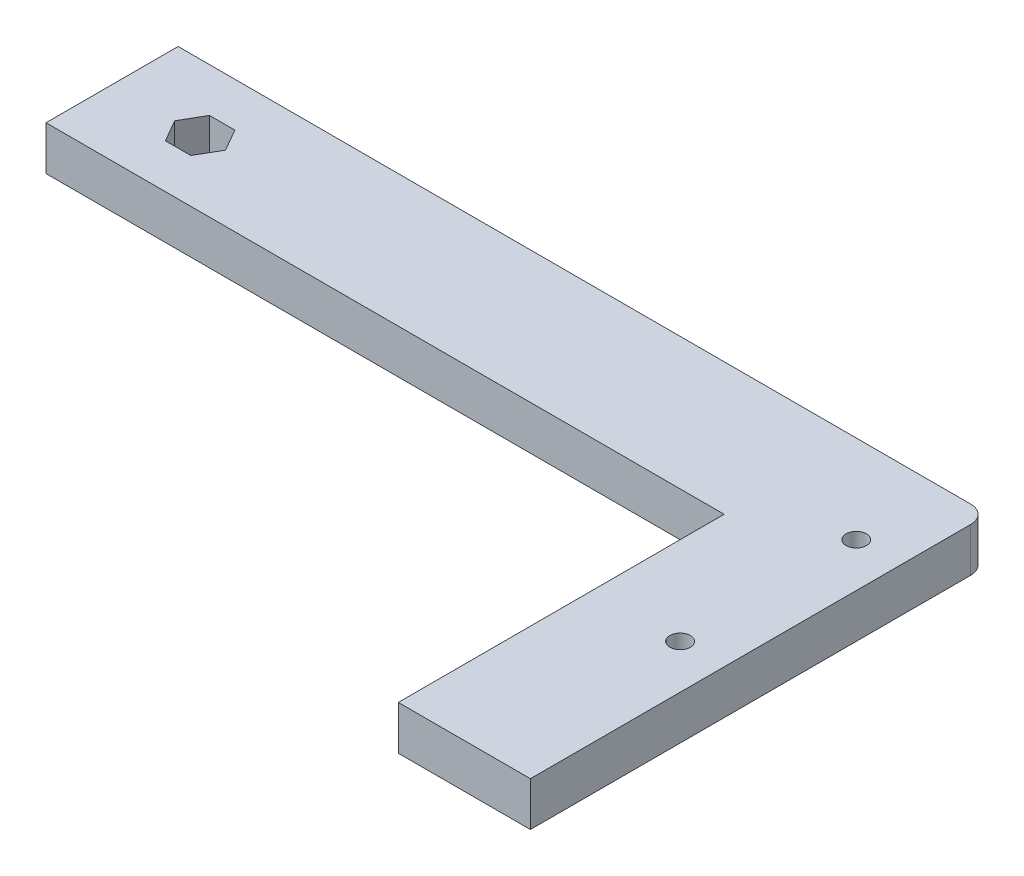
SolidWorks part; units mm, degrees
material "Acrylic (Medium-high impact)"
ref_plane "Front Plane" through (0, 0, 0) normal (0, 0, 1) x (1, 0, 0)
ref_plane "Top Plane" through (0, 0, 0) normal (0, 1, 0) x (1, 0, 0)
ref_plane "Right Plane" through (0, 0, 0) normal (1, 0, 0) x (0, 0, -1)
sketch "Sketch1" plane through (0, 0, 0) normal (0, 1, 0) x (1, 0, 0)
  line L0 (0, 0) -> (114.3, 0)
  line L1 (116.84, -2.54) -> (116.84, -66.04)
  line L2 (0, -19.05) -> (97.79, -19.05)
  line L3 (97.79, -19.05) -> (97.79, -66.04)
  line L4 (0, 0) -> (0, -19.05)
  line L5 (97.79, -19.05) -> (97.79, -66.04) construction
  line L6 (97.79, -66.04) -> (116.84, -66.04)
  arc A0 (114.3, 0) -> (116.84, -2.54) centre (114.3, -2.54) cw
  arc A1 (97.79, -19.05) -> (97.79, -19.05) centre (97.79, -19.05) cw
  dimension "D1" = 2.54
  dimension "D2" = 114.3
  dimension "D3" = 63.5
  dimension "D5" = 90
  dimension "D4" = 19.05
extrude "Boss-Extrude1" add sketch "Sketch1" along normal blind 6.35
sketch "Sketch2" plane through (0, 6.35, 0) normal (0, 1, 0) x (1, 0, 0)
  line L0 (0, 0) -> (0, -19.05) construction
  line L1 (114.3, 0) -> (0, 0) construction
  line L2 (14.5331, -12.7) -> (16.3662, -9.525)
  line L3 (16.3662, -9.525) -> (14.5331, -6.35)
  line L4 (14.5331, -6.35) -> (10.8669, -6.35)
  line L5 (10.8669, -6.35) -> (9.0338, -9.525)
  line L6 (9.0338, -9.525) -> (10.8669, -12.7)
  line L7 (10.8669, -12.7) -> (14.5331, -12.7)
  dimension "D1" = 3.6662
  dimension "D2" = 9.0338
  dimension "D3" = 6.35
extrude "Cut-Extrude1" cut sketch "Sketch2" against normal through all
sketch "Sketch3" plane through (0, 0, 0) normal (0, -1, 0) x (1, 0, 0)
  line L1 (114.3, 0) -> (0, 0) construction
  line L2 (97.79, 19.05) -> (97.79, 66.04) construction
  circle A0 centre (110.49, 38.1) radius 1.4732
  circle A1 centre (110.49, 12.7) radius 1.4732
  dimension "D1" = 2.9464
  dimension "D2" = 2.9464
  dimension "D3" = 38.1
  dimension "D4" = 12.7
  dimension "D5" = 12.7
  dimension "D6" = 12.7
extrude "Cut-Extrude2" cut sketch "Sketch3" against normal through all
